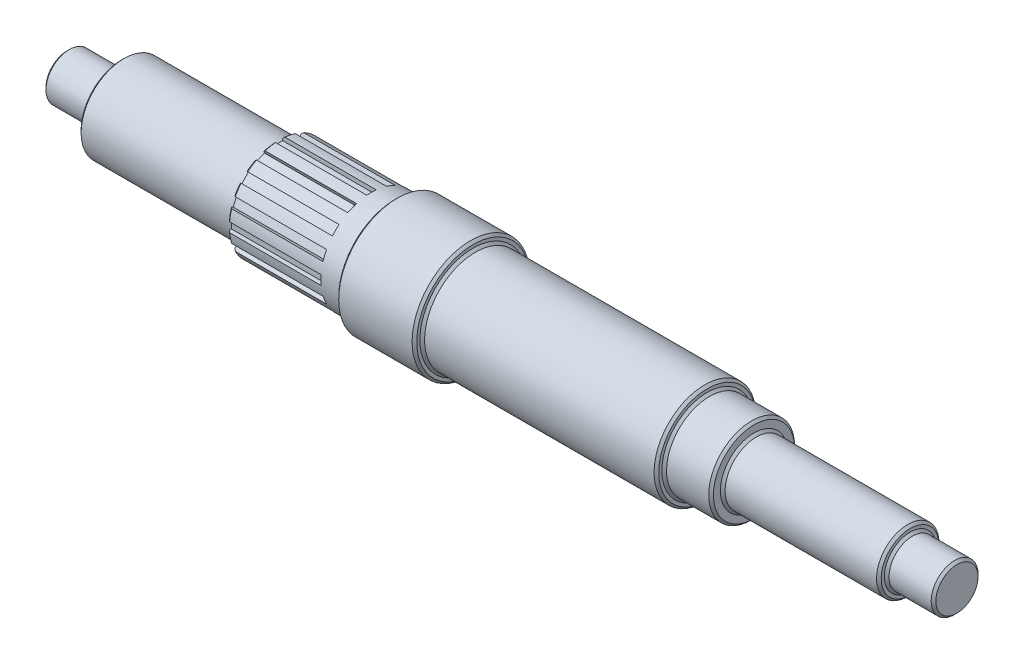
SolidWorks part; units mm, degrees
material "ABS"
ref_plane "Płaszczyzna przednia" through (0, 0, 0) normal (0, 0, 1) x (1, 0, 0)
ref_plane "Płaszczyzna górna" through (0, 0, 0) normal (0, 1, 0) x (1, 0, 0)
ref_plane "Płaszczyzna prawa" through (0, 0, 0) normal (1, 0, 0) x (0, 0, -1)
sketch "Szkic1" plane through (0, 0, 0) normal (0, 0, 1) x (1, 0, 0)
  line L0 (0, 0) -> (1140, 0) construction
  line L1 (0, 0) -> (0, 30)
  line L2 (0, 30) -> (70, 30)
  line L3 (70, 30) -> (70, 55)
  line L4 (70, 55) -> (270, 55)
  line L5 (270, 55) -> (270, 65)
  line L6 (270, 65) -> (420, 65)
  line L7 (420, 65) -> (420, 75)
  line L8 (420, 75) -> (520, 75)
  line L9 (520, 75) -> (520, 65)
  line L10 (520, 65) -> (820, 65)
  line L11 (820, 65) -> (820, 55)
  line L12 (820, 55) -> (880, 55)
  line L13 (880, 55) -> (880, 40)
  line L14 (880, 40) -> (1080, 40)
  line L15 (1080, 40) -> (1080, 30)
  line L16 (1080, 30) -> (1140, 30)
  line L17 (1140, 30) -> (1140, 0)
  line L18 (0, 0) -> (1140, 0)
  point P21 (170, 55)
  point P22 (70, 42.5)
  point P23 (1080, 35)
  point P24 (520, 70)
  dimension "D1" = 30
  dimension "D2" = 55
  dimension "D3" = 65
  dimension "D4" = 75
  dimension "D5" = 55
  dimension "D6" = 40
  dimension "D7" = 1140
  dimension "D8" = 70
  dimension "D9" = 60
  dimension "D10" = 200
  dimension "D11" = 60
  dimension "D12" = 300
  dimension "D13" = 150
  dimension "D14" = 200
revolve "Obrót1" add sketch "Szkic1" angle 360 about L0
ref_plane "Płaszczyzna2" through (0, -55, 0) normal (0, -1, 0) x (-1, 0, 0)
sketch "Szkic2" plane through (0, -55, 0) normal (0, -1, 0) x (-1, 0, 0)
  line L0 (-70, 0) -> (-270, 0) construction
  line L2 (-70, -55) -> (-70, 55) construction
  line L3 (-270, -65) -> (-270, 65) construction
  line L4 (-170, 0) -> (-170, 55) construction
  line L5 (-70, 55) -> (-270, 55) construction
  line L6 (-210, 0) -> (-130, 0) construction
  line L7 (-210, 12) -> (-130, 12)
  line L8 (-210, -12) -> (-130, -12)
  arc A0 (-210, 12) -> (-210, -12) centre (-210, 0) ccw
  arc A1 (-130, -12) -> (-130, 12) centre (-130, 0) ccw
  point P13 (-170, 0)
  dimension "D1" = 80
  dimension "D2" = 24
extrude "Wytnij-wyciągnięcie1" cut sketch "Szkic2" against normal blind 22 contours L8 A1 L7 A0
ref_plane "Płaszczyzna5" through (270, 0, 0) normal (-1, 0, 0) x (0, 0, 1)
sketch "Szkic4" plane through (270, 0, 0) normal (-1, 0, 0) x (0, 0, 1)
  line L0 (0, 0) -> (0, -71.3483) construction
  line L1 (0, -65.1354) -> (0, -59.3483)
  line L2 (0, -59.3483) -> (-6, -59.3483)
  line L3 (0, -59.3483) -> (6, -59.3483)
  line L4 (-6, -59.3483) -> (-6, -71.3483)
  line L5 (-6, -71.3483) -> (6, -71.3483)
  line L6 (6, -71.3483) -> (6, -59.3483)
  dimension "D1" = 12
extrude "Wytnij-wyciągnięcie2" cut sketch "Szkic4" against normal blind 120 contours L0 L1 L2 L4 L5 | L1 L0 L5 L6 L3
pattern_circular "Szyk kołowy2" count 16 over 360 about axis through (0, 0, 0) along (1, 0, 0) of "Wytnij-wyciągnięcie2"
chamfer "Sfazowanie1" distance 3 angle 45 31 edges at (1140, -30, 0) (1080, -30, 0) (1080, -40, 0) (880, -40, 0) (880, -55, 0) (820, -55, 0) (820, -65, 0) (520, -65, 0) (520, -75, 0) (420, -75, 0) (420, -65, 0) (270, 63.751, 12.6809) (270, 54.0455, 36.1121) (270, 36.1121, 54.0455) (270, 12.6809, 63.751) (270, -12.6809, 63.751) (270, -36.1121, 54.0455) (270, -54.0455, 36.1121) (270, -63.751, 12.6809) (270, -63.751, -12.6809) (270, -54.0455, -36.1121) (270, -36.1121, -54.0455) (270, -12.6809, -63.751) (270, 12.6809, -63.751) (270, 36.1121, -54.0455) (270, 54.0455, -36.1121) (270, 63.751, -12.6809) (270, -55, 0) (70, -55, 0) (70, -30, 0) (0, -30, 0)
